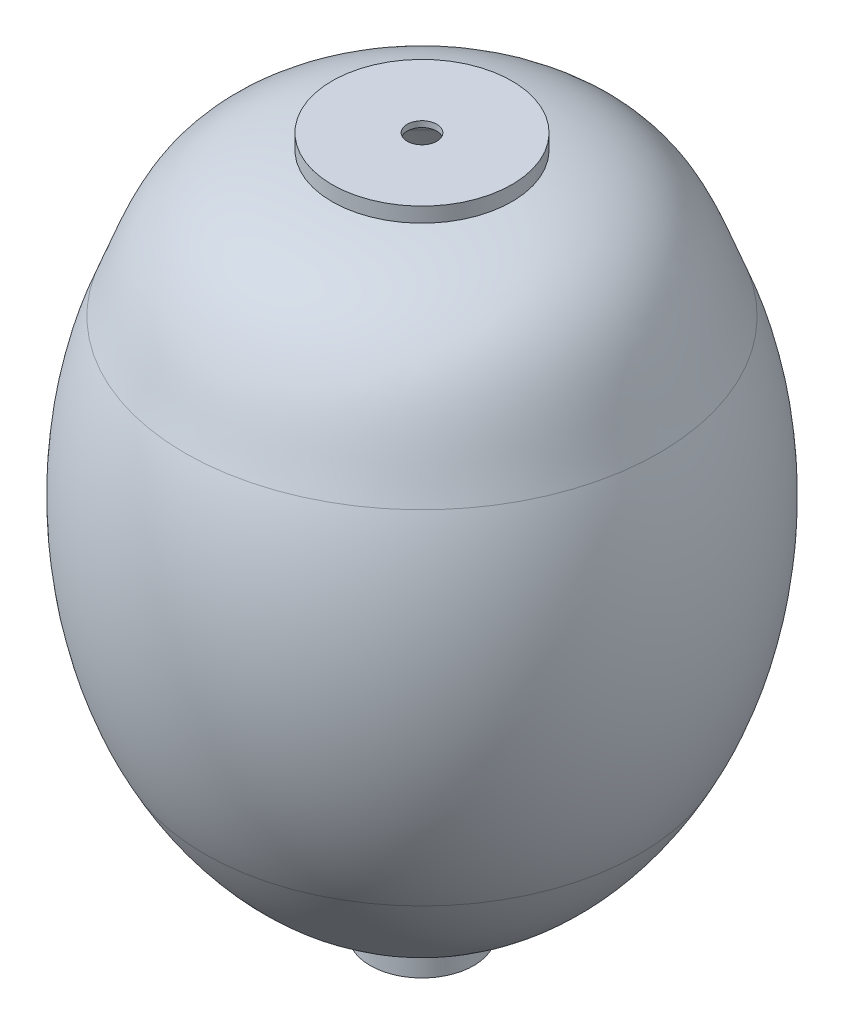
SolidWorks part; units mm, degrees
ref_plane "front plane" through (0, 0, 0) normal (0, 0, 1) x (1, 0, 0)
ref_plane "top plane" through (0, 0, 0) normal (0, 1, 0) x (1, 0, 0)
ref_plane "Plan de droite" through (0, 0, 0) normal (1, 0, 0) x (0, 0, -1)
sketch "Sketch2" plane through (0, 0, 0) normal (0, 0, -1) x (-1, 0, 0)
  line L0 (0, 7.2136) -> (0, -235) construction
  line L1 (-17.5, -223) -> (-17.5, -235)
  line L2 (-89.6124, -101.3414) -> (-89.6124, -24.8868) construction
  line L3 (-30.3734, 0) -> (-30.3734, -5)
  line L4 (0, 0) -> (0, -235)
  line L6 (0, 0) -> (-30.3734, 0)
  line L432 (-17.5, -235) -> (0, -235)
  spline S0 degree 3 poles (-30.3734, -5) (-68.2556, -11.3816) (-71.5642, -32.4574) (-80.0881, -53.7125) knots 0 0 0 0 0.756783 0.756783 0.756783 0.756783
  spline S11 degree 3 poles (-80.0881, -53.7125) (-80.7103, -55.264) (-81.2742, -56.7652) (-82.3148, -59.6971) (-82.7912, -61.1275) (-83.6747, -63.9359) (-84.0816, -65.3139) (-84.8376, -68.0298) (-85.1866, -69.3677) (-85.8352, -72.0125) (-86.1347, -73.3193) (-86.6901, -75.9085) (-86.946, -77.1908) (-87.6546, -81.009) (-88.049, -83.5163) (-88.7047, -88.4854) (-88.9658, -90.9469) (-89.217, -94.009) (-89.2635, -94.6207) (-89.3488, -95.8397) (-89.3877, -96.4475) (-89.4933, -98.2661) (-89.549, -99.4724) (-89.6739, -103.076) (-89.7011, -105.4583) (-89.649, -110.1994) (-89.5698, -112.5581) (-89.3066, -117.2664) (-89.1226, -119.6159) (-88.6475, -124.3199) (-88.3564, -126.6743) (-87.6604, -131.4032) (-87.2556, -133.7776) (-86.3199, -138.5644) (-85.7892, -140.9766) (-85.0345, -144.0302) (-84.8789, -144.6428) (-84.5582, -145.8725) (-84.3929, -146.4898) (-83.8825, -148.3464) (-83.5236, -149.5883) (-82.7648, -152.084) (-82.365, -153.3378) (-81.5196, -155.862) (-81.0741, -157.1323) (-80.131, -159.6954) (-79.6335, -160.9881) (-78.5776, -163.6036) (-78.0193, -164.9262) (-76.8292, -167.6122) (-76.1976, -168.9754) (-74.8903, -171.6589) (-74.2211, -172.9751) (-73.4999, -174.3255) knots 422.815435 422.815435 422.815435 422.815435 427.264786 427.264786 431.714136 431.714136 436.163487 436.163487 440.612837 440.612837 445.062188 445.062188 449.511538 449.511538 458.410241 458.410241 467.308941 467.308941 469.533617 469.533617 471.758292 471.758292 476.207642 476.207642 485.106343 485.106343 494.005044 494.005044 502.903747 502.903747 511.802448 511.802448 520.701148 520.701148 529.599849 529.599849 531.824525 531.824525 534.0492 534.0492 538.49855 538.49855 542.947902 542.947902 547.397253 547.397253 551.846603 551.846603 556.295954 556.295954 560.745304 560.745304 564.877542 564.877542 564.877542 564.877542
  spline S12 degree 3 poles (-73.4999, -174.3255) (-70.7099, -179.5491) (-67.6163, -184.5373) (-62.47, -191.6277) (-60.6698, -193.9255) (-56.8829, -198.3765) (-54.8964, -200.5299) (-51.7574, -203.6366) (-50.6845, -204.6515) (-49.0318, -206.1404) (-48.4729, -206.6318) (-47.3447, -207.5988) (-46.7756, -208.0744) (-43.9039, -210.4117) (-41.5239, -212.1521) (-36.5799, -215.3456) (-34.0165, -216.7995) (-30.6843, -218.4166) (-30.0114, -218.73) (-28.6523, -219.336) (-27.9657, -219.6286) (-24.0774, -221.2092) (-20.8188, -222.2428) (-17.5, -223) knots 0 0 0 0 0.25 0.25 0.375 0.375 0.5 0.5 0.5625 0.5625 0.59375 0.59375 0.625 0.625 0.75 0.75 0.875 0.875 0.90625 0.90625 0.9375 0.9375 1.082855 1.082855 1.082855 1.082855
  dimension "D1" = 5
  dimension "D2" = 12
  dimension "D3" = 235
  dimension "D4" = 17.5
revolve "Revolve2" add sketch "Sketch2" angle 360 about L4
shell "Shell3" thickness 2
sketch "Sketch3" plane through (0, 0, 0) normal (0, 1, 0) x (1, 0, 0)
  circle A0 centre (0, 0) radius 5
extrude "Cut-Extrude1" cut sketch "Sketch3" against normal blind 15
